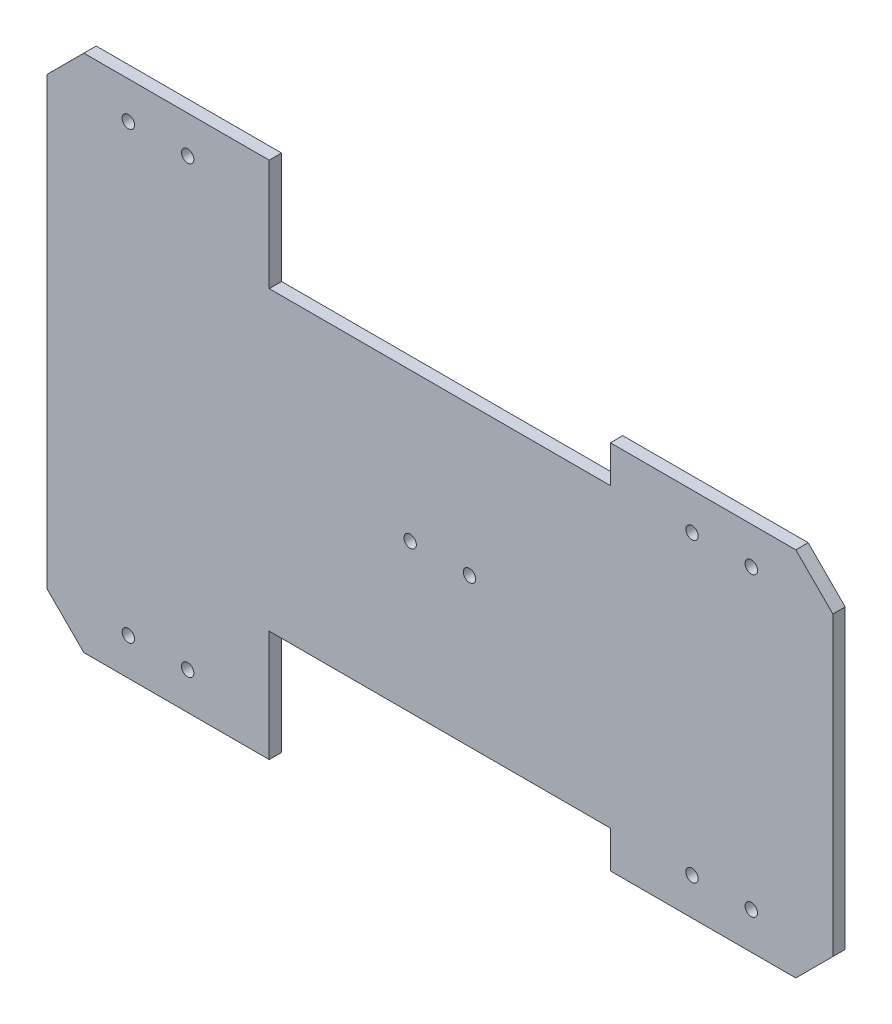
SolidWorks part; units mm, degrees
ref_plane "前视基准面" through (0, 0, 0) normal (0, 0, 1) x (1, 0, 0)
ref_plane "上视基准面" through (0, 0, 0) normal (0, 1, 0) x (1, 0, 0)
ref_plane "右视基准面" through (0, 0, 0) normal (1, 0, 0) x (0, 0, -1)
ref_plane "基准面4" through (0, 0, 5) normal (0, 0, 1) x (1, 0, 0)
sketch "草图1" plane through (0, 0, 5) normal (0, 0, 1) x (1, 0, 0)
  line L0 (15.93, -70) -> (15.93, -85)
  line L1 (15.93, -85) -> (90.93, -85)
  line L2 (90.93, -85) -> (105.93, -70)
  line L3 (105.93, -70) -> (105.93, 50)
  line L4 (105.93, 50) -> (90.93, 65)
  line L5 (90.93, 65) -> (15.93, 65)
  line L6 (15.93, 65) -> (15.93, 50)
  line L7 (15.93, 50) -> (-122.07, 50)
  line L8 (-122.07, 50) -> (-122.07, 95)
  line L9 (-122.07, 95) -> (-197.07, 95)
  line L10 (-197.07, 95) -> (-212.07, 80)
  line L11 (-212.07, 80) -> (-212.07, -100)
  line L12 (-212.07, -100) -> (-197.07, -115)
  line L13 (-197.07, -115) -> (-122.07, -115)
  line L14 (-122.07, -115) -> (-122.07, -70)
  line L15 (-122.07, -70) -> (15.93, -70)
  circle A0 centre (-179.07, 80) radius 2.5
  circle A1 centre (-179.07, -100) radius 2.5
  circle A2 centre (72.93, -70) radius 2.5
  circle A3 centre (48.93, 50) radius 2.5
  circle A6 centre (-155.07, 80) radius 2.5
  circle A7 centre (-155.07, -100) radius 2.5
  circle A8 centre (-65.07, -10) radius 2.5
  circle A9 centre (-41.07, -10) radius 2.5
  circle A10 centre (72.93, 50) radius 2.5
  circle A11 centre (48.93, -70) radius 2.5
  dimension "D3" = 135
  dimension "D4" = 5
  dimension "D5" = 24
  dimension "D7" = 24
  dimension "D8" = 5
  dimension "D9" = 5
  dimension "D10" = 5
  dimension "D11" = 5
  dimension "D12" = 24
  dimension "D6" = 24
  dimension "D2" = 135
  dimension "D14" = 135
  dimension "D16" = 135
  dimension "D17" = 120
  dimension "D18" = 210
  dimension "D20" = 90
  dimension "D21" = 75
extrude "凸台-拉伸1" add sketch "草图1" against normal blind 5
ref_plane "基准面5" through (-132.57, 35, 5) normal (0, -1, 0) x (-1, 0, 0)
